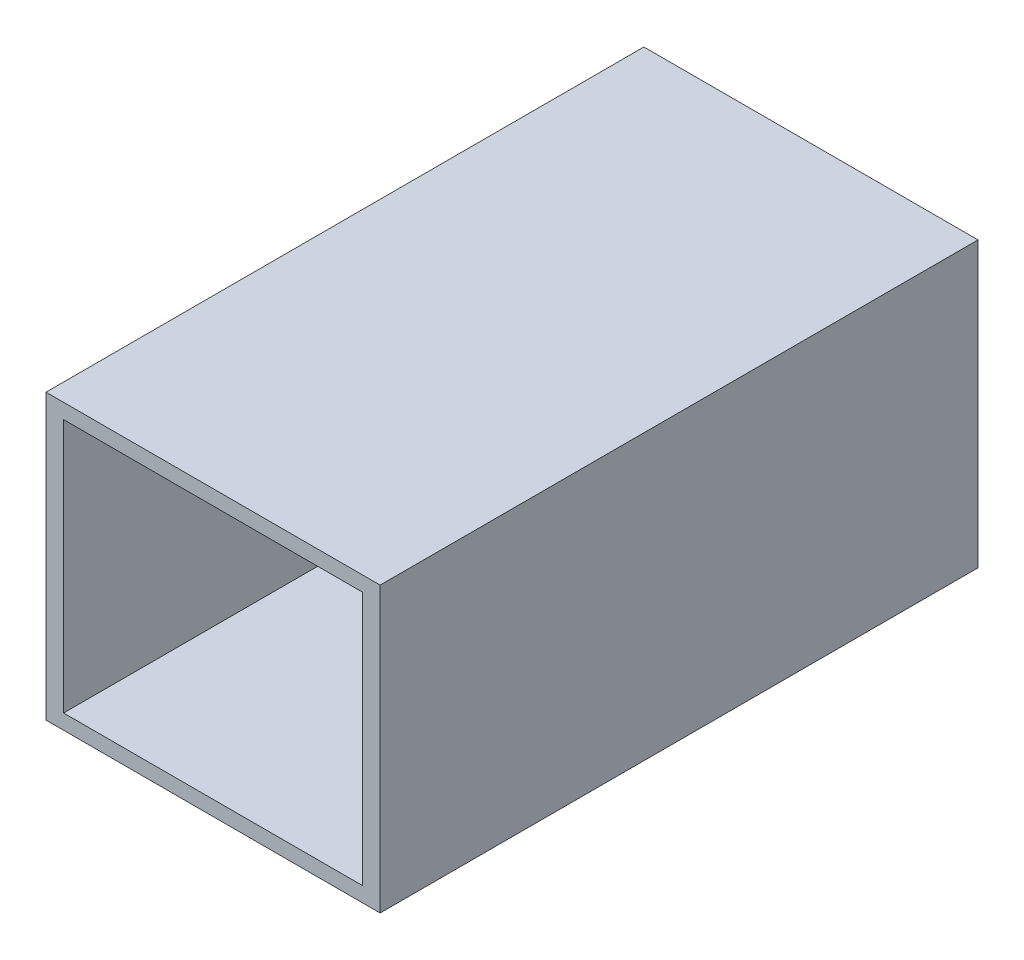
SolidWorks part; units mm, degrees
ref_plane "Front Plane" through (0, 0, 0) normal (0, 0, 1) x (1, 0, 0)
ref_plane "Top Plane" through (0, 0, 0) normal (0, 1, 0) x (1, 0, 0)
ref_plane "Right Plane" through (0, 0, 0) normal (1, 0, 0) x (0, 0, -1)
sketch "Sketch1" plane through (0, 0, 0) normal (0, 0, 1) x (1, 0, 0)
  line L1 (-141.9412, 120.65) -> (141.9412, 120.65)
  line L2 (-141.9412, 120.65) -> (-141.9412, -120.65)
  line L3 (-141.9412, -120.65) -> (141.9412, -120.65)
  line L4 (141.9412, 120.65) -> (141.9412, -120.65)
  line L5 (-141.9412, 120.65) -> (141.9412, -120.65) construction
  line L6 (-141.9412, -120.65) -> (141.9412, 120.65) construction
  line L7 (-127, 107.95) -> (127, 107.95)
  line L8 (-127, 107.95) -> (-127, -107.95)
  line L9 (-127, -107.95) -> (127, -107.95)
  line L10 (127, 107.95) -> (127, -107.95)
  line L11 (-127, 107.95) -> (127, -107.95) construction
  line L12 (-127, -107.95) -> (127, 107.95) construction
  point P0 (0, 0)
  point P6 (0, 0)
  dimension "D1" = 254
  dimension "D2" = 215.9
  dimension "D3" = 12.7
extrude "Boss-Extrude1" add sketch "Sketch1" along normal blind 508
